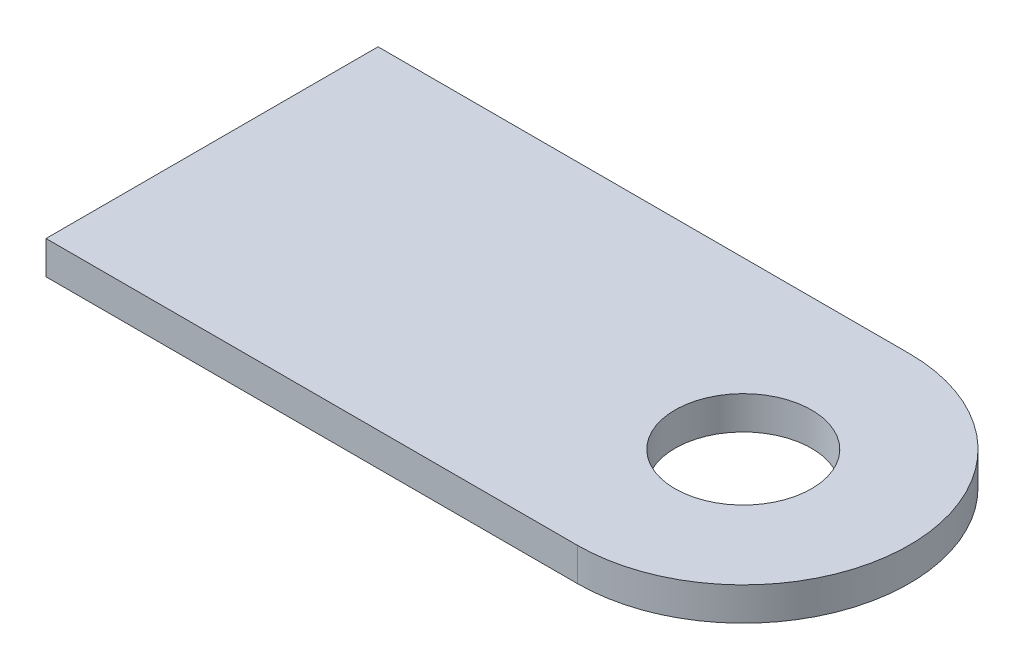
SolidWorks part; units mm, degrees
ref_plane "Front Plane" through (0, 0, 0) normal (0, 0, 1) x (1, 0, 0)
ref_plane "Top Plane" through (0, 0, 0) normal (0, 1, 0) x (1, 0, 0)
ref_plane "Right Plane" through (0, 0, 0) normal (1, 0, 0) x (0, 0, -1)
sketch "Sketch1" plane through (0, 0, 0) normal (0, 1, 0) x (1, 0, 0)
  line L0 (-25.4, 7.9375) -> (0, 7.9375)
  line L1 (0, -7.9375) -> (-25.4, -7.9375)
  line L2 (-25.4, -7.9375) -> (-25.4, 7.9375)
  circle A0 centre (0, 0) radius 3.2639
  arc A1 (0, 7.9375) -> (0, -7.9375) centre (0, 0) cw
  point P7 (1.5093, -1.6353)
  point P9 (-25.4477, -9.525)
  dimension "D1" = 6.5278
  dimension "D2" = 15.875
  dimension "D3" = 25.4
extrude "Boss-Extrude1" add sketch "Sketch1" along normal blind 1.5875
